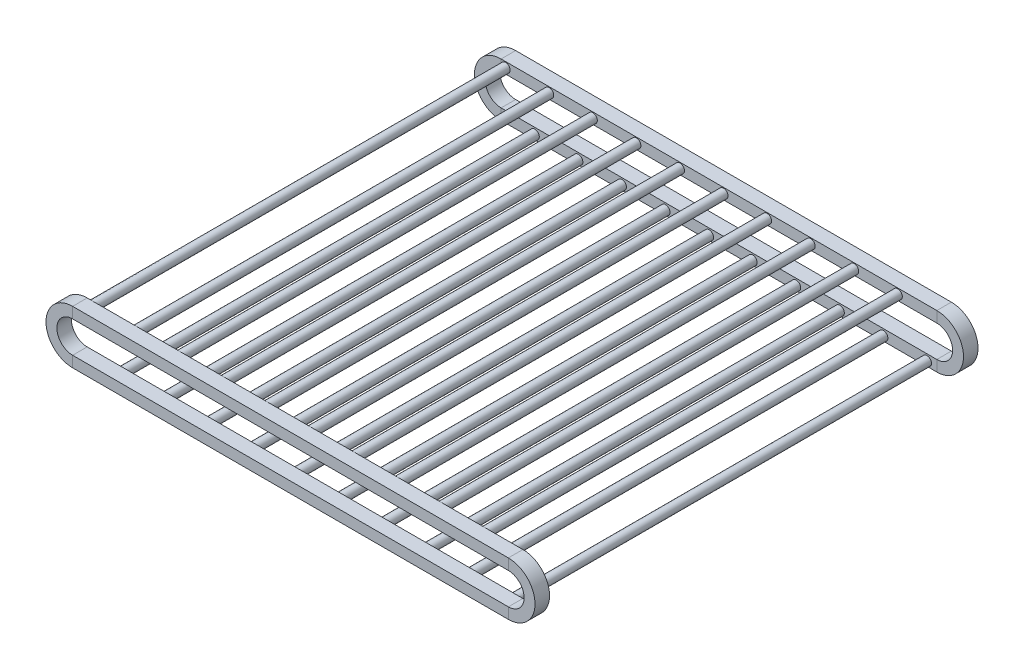
SolidWorks part; units mm, degrees
ref_plane "Front Plane" through (0, 0, 0) normal (0, 0, 1) x (1, 0, 0)
ref_plane "Top Plane" through (0, 0, 0) normal (0, 1, 0) x (1, 0, 0)
ref_plane "Right Plane" through (0, 0, 0) normal (1, 0, 0) x (0, 0, -1)
sketch "Sketch2" plane through (0, 0, 0) normal (0, 0, 1) x (1, 0, 0)
  line L0 (0, 0) -> (1, 0) construction
  line L1 (0, 0) -> (0, 1) construction
  line L2 (0, 50) -> (1200, 50)
  line L3 (1200, -50) -> (0, -50)
  arc A0 (0, -50) -> (0, 50) centre (0, 0) cw
  arc A1 (1200, 50) -> (1200, -50) centre (1200, 0) cw
ref_plane "Plane1" through (0, 0, 0) normal (1, 0, 0) x (0, 0, -1)
sketch "Sketch3" plane through (0, 0, 0) normal (1, 0, 0) x (0, 0, -1)
  line L0 (0, 50) -> (0, -50) construction
  line L1 (-20, 73.3637) -> (20, 73.3637)
  line L2 (-20, 73.3637) -> (-20, 43.3637)
  line L3 (-20, 43.3637) -> (20, 43.3637)
  line L4 (20, 73.3637) -> (20, 43.3637)
  point P4 (0, 43.3637)
  dimension "D1" = 40
  dimension "D2" = 30
  dimension "D3" = 0
sweep "Sweep1" add profiles "Sketch3" path "Sketch2"
sketch "Sketch4" plane through (0, 0, -20) normal (0, 0, -1) x (-1, 0, 0)
  circle A0 centre (-1092.451, 58.9612) radius 12.5
  dimension "D1" = 25
extrude "Boss-Extrude1" add sketch "Sketch4" along normal blind 1180
pattern_linear "LPattern1" count 10 spacing 120 along (-1, 0, 0) of "Boss-Extrude1"
pattern_linear "LPattern2" count 2 spacing 1180 along (0, 0, -1) of "Sweep1"
sketch "Sketch5" plane through (0, 0, -20) normal (0, 0, -1) x (-1, 0, 0)
  circle A0 centre (-1172.6811, -60.135) radius 12.5
  dimension "D1" = 25
extrude "Boss-Extrude2" add sketch "Sketch5" along normal blind 1170 contours A0
pattern_linear "LPattern3" count 10 spacing 120 along (-1, 0, 0) of "Boss-Extrude2"
